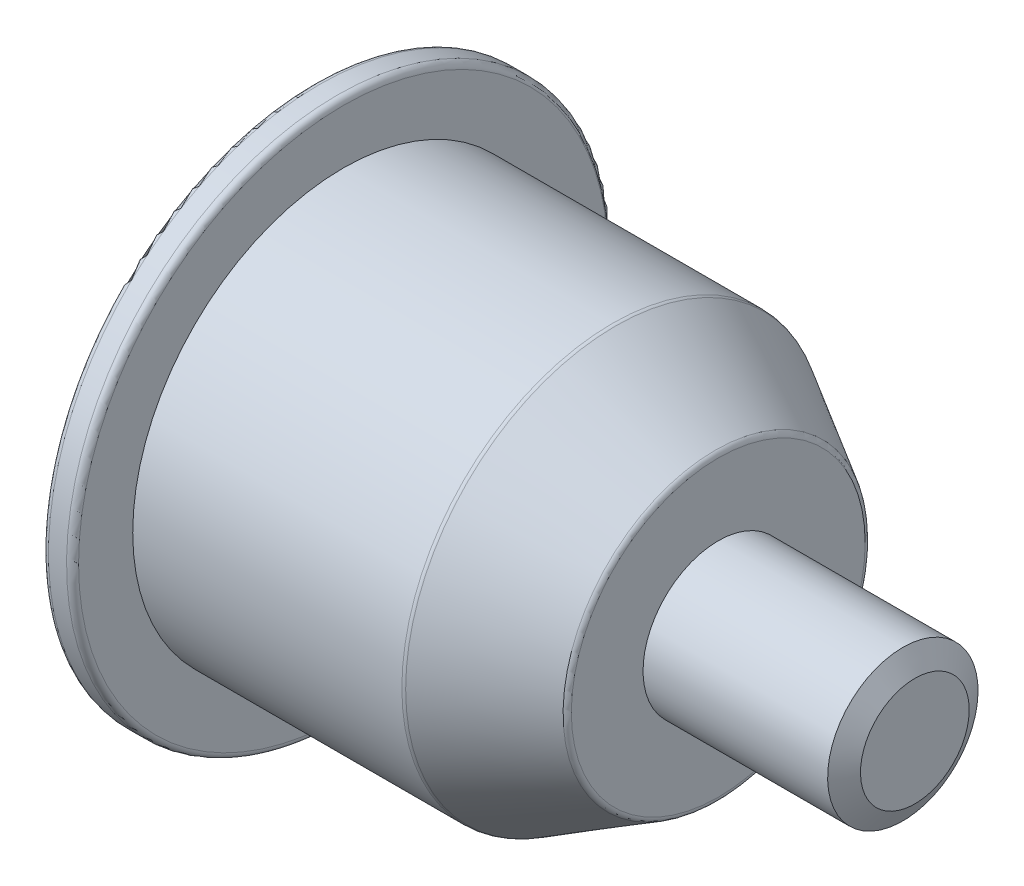
SolidWorks part; units mm, degrees
ref_plane "Front Plane" through (0, 0, 0) normal (0, 0, 1) x (1, 0, 0)
ref_plane "Top Plane" through (0, 0, 0) normal (0, 1, 0) x (1, 0, 0)
ref_plane "Right Plane" through (0, 0, 0) normal (1, 0, 0) x (0, 0, -1)
sketch "Sketch1" plane through (0, 0, 0) normal (0, 0, 1) x (1, 0, 0)
  line L0 (0, 228.6) -> (25.4, 228.6)
  line L1 (25.4, 228.6) -> (25.4, 177.8)
  line L2 (25.4, 177.8) -> (254, 177.8)
  line L4 (341.9882, 63.5) -> (508, 63.5)
  line L5 (508, 63.5) -> (508, 0)
  line L6 (508, 0) -> (279.4, 0)
  line L7 (279.4, 0) -> (279.4, 63.5)
  line L8 (279.4, 63.5) -> (152.4, 63.5)
  line L9 (152.4, 63.5) -> (152.4, 127)
  line L10 (152.4, 127) -> (0, 127)
  line L11 (0, 127) -> (0, 228.6)
  line L12 (341.9882, 63.5) -> (341.9882, 127)
  line L13 (341.9882, 127) -> (254, 177.8)
  dimension "D1" = 63.5
  dimension "D2" = 127
  dimension "D3" = 177.8
  dimension "D4" = 50.8
  dimension "D5" = 25.4
  dimension "D6" = 152.4
  dimension "D7" = 254
  dimension "D8" = 279.4
  dimension "D9" = 508
  dimension "D10" = 30
  dimension "D11" = 63.5
  dimension "D12" = 127
revolve "Revolve1" add sketch "Sketch1" angle 360 about L6
fillet "Fillet1" radius 5.08 4 edges at (341.9882, 127, 0) (254, 177.8, 0) (25.4, 228.6, 0) (0, 228.6, 0)
fillet "Fillet2" radius 12.7 4 edges at (279.4, 63.5, 0) (152.4, 63.5, 0) (152.4, 127, 0) (0, 127, 0)
chamfer "Chamfer1" distance 10.16 angle 60 1 edges at (508, 63.5, 0)
